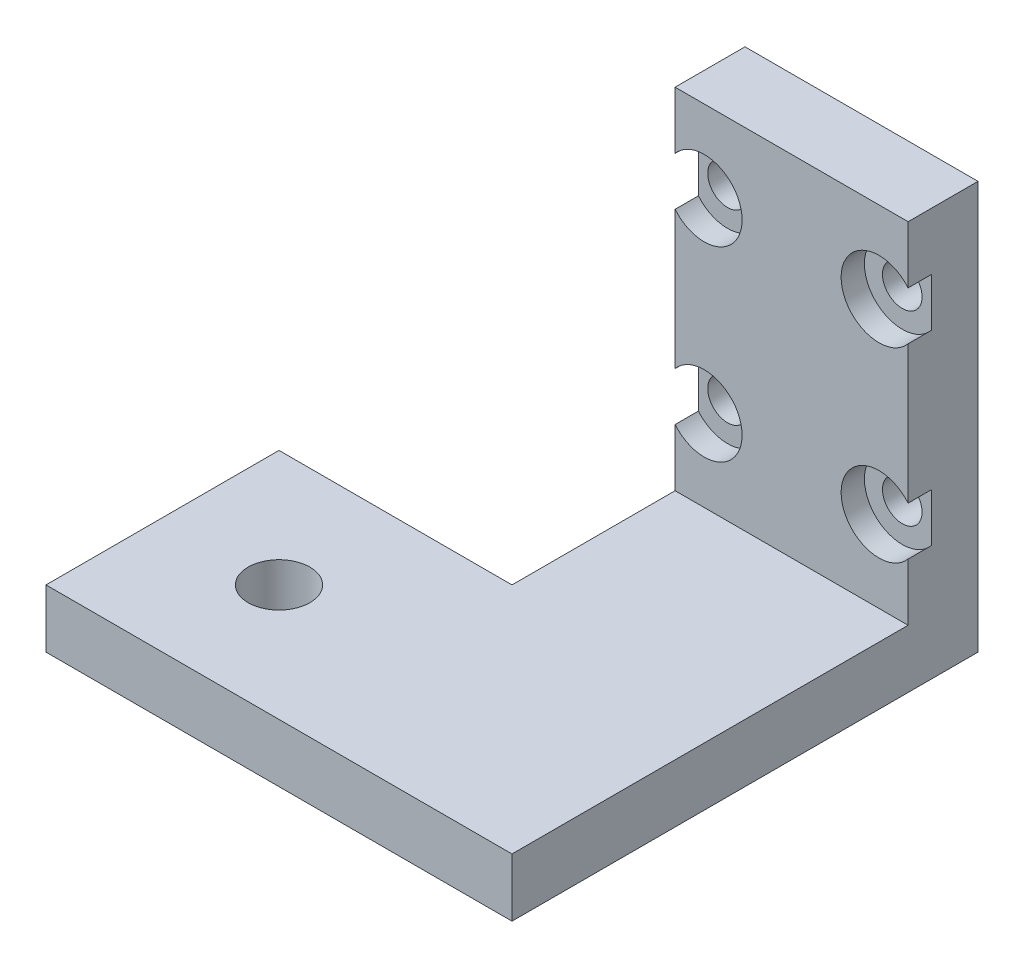
SolidWorks part; units mm, degrees
material "ABS"
ref_plane "Alzado" through (0, 0, 0) normal (0, 0, 1) x (1, 0, 0)
ref_plane "Planta" through (0, 0, 0) normal (0, 1, 0) x (1, 0, 0)
ref_plane "Vista lateral" through (0, 0, 0) normal (1, 0, 0) x (0, 0, -1)
sketch "Sketch1" plane through (0, 0, 0) normal (0, 1, 0) x (1, 0, 0)
  line L1 (0, 0) -> (-20, 0)
  line L2 (0, 0) -> (0, -20) construction
  line L3 (0, -20) -> (-20, -20)
  line L4 (-20, 0) -> (-20, -20)
  line L5 (0, 0) -> (20, 0) construction
  line L7 (0, -20) -> (20, -20)
  line L8 (20, 0) -> (20, -20)
  line L10 (20, 0) -> (20, 20)
  line L11 (20, 20) -> (0, 20)
  line L12 (0, 0) -> (0, 20)
  dimension "D1" = 20
  dimension "D2" = 20
  dimension "D3" = 20
  dimension "D4" = 20
extrude "Boss-Extrude1" add sketch "Sketch1" against normal blind 5
sketch "Sketch2" plane through (0, 0, 0) normal (0, 1, 0) x (1, 0, 0)
  line L0 (0, 20) -> (0, 0) construction
  line L1 (20, 20) -> (0, 20)
  line L2 (20, 20) -> (20, 14)
  line L3 (20, 14) -> (0, 14)
  line L4 (0, 20) -> (0, 14)
  dimension "D1" = 6
extrude "Boss-Extrude2" add sketch "Sketch2" along normal blind 30
sketch "Sketch3" plane through (0, 0, -14) normal (0, 0, 1) x (1, 0, 0)
  line L0 (10, -970) -> (10, 49030) construction
  line L1 (0, 30) -> (20, 30) construction
  line L2 (-1000, 15) -> (49000, 15) construction
  line L3 (0, 30) -> (0, 0) construction
  circle A0 centre (2.5, 7) radius 1.5
  circle A1 centre (2.5, 23) radius 1.5
  circle A2 centre (17.5, 7) radius 1.5
  circle A3 centre (17.5, 23) radius 1.5
  point P5 (10, 30)
  point P10 (0, 15)
  dimension "D3" = 3
  dimension "D1" = 8
  dimension "D2" = 7.5
extrude "Cut-Extrude1" cut sketch "Sketch3" against normal through all
hole_wizard "Refrentado para tornillo con cabeza plana de M31" positions "Sketch4" profile "Sketch6" counterbore size "M3" standard "ISO" end condition through all
sketch "Sketch4" plane through (0, 0, -14) normal (0, 0, 1) x (1, 0, 0)
  point P0 (2.5, 23)
  point P3 (2.5, 7)
  point P6 (17.5, 7)
  point P9 (17.5, 23)
sketch "Sketch6" plane through (2.5, 23, -14) normal (1, 0, 0) x (0, -1, 0)
  line L0 (0, 0) -> (0, 6)
  line L1 (0, 6) -> (1.7, 6)
  line L3 (1.7, 6) -> (1.7, 2)
  line L4 (1.7, 2) -> (3.25, 2)
  line L5 (3.25, 2) -> (3.25, 0)
  line L7 (3.25, 0) -> (0, 0)
  line L11 (0, -6.35) -> (0, 107.95) construction
  dimension "Diámetro de taladro hasta el siguiente" = 3.4
  dimension "Profundidad de taladro hasta el siguiente" = 6
  dimension "Diámetro de refrentado" = 6.5
  dimension "Profundidad de refrentado" = 2
sketch "Sketch7" plane through (0, -5, 0) normal (0, -1, 0) x (1, 0, 0)
  line L0 (-20, 20) -> (0, 0) construction
  line L1 (0, 0) -> (0, 20) construction
  line L2 (-20, 20) -> (20, 20) construction
  line L3 (0, 20) -> (-20, 0) construction
  circle A0 centre (-10, 10) radius 2.5
  dimension "D1" = 5
extrude "Cut-Extrude2" cut sketch "Sketch7" against normal up to next
sketch "Sketch8" plane through (0, -5, 0) normal (0, -1, 0) x (-1, 0, 0)
  point P0 (10, -10)
hole_wizard "Taladro de margen para M51" positions "Sketch8" profile "Sketch10" hole size "M5" standard "ISO"
sketch "Sketch10" plane through (-10, -5, 10) normal (1, 0, 0) x (0, 0, -1)
  line L0 (0, 0) -> (0, 6.5923)
  line L1 (0, 6.5923) -> (2.65, 5)
  line L2 (2.65, 5) -> (2.65, 0)
  line L5 (2.65, 0) -> (0, 0)
  line L10 (0, 6.5923) -> (-2.65, 5) construction
  line L11 (0, -6.35) -> (0, 107.95) construction
  dimension "Diámetro de taladro" = 5.3
  dimension "Profundidad de taladro" = 5
  dimension "Ángulo de perforador" = 118
